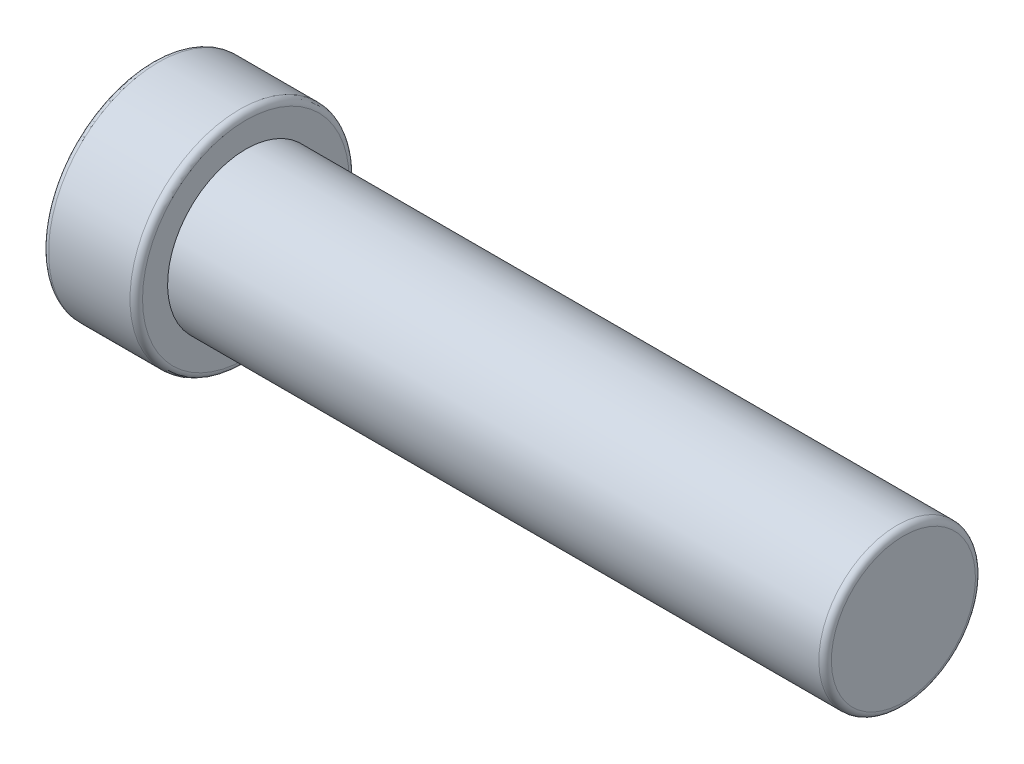
SolidWorks part; units mm, degrees
ref_plane "Ön Düzlem" through (0, 0, 0) normal (0, 0, 1) x (1, 0, 0)
ref_plane "Üst Düzlem" through (0, 0, 0) normal (0, 1, 0) x (1, 0, 0)
ref_plane "Sağ Düzlem" through (0, 0, 0) normal (1, 0, 0) x (0, 0, -1)
sketch "Sketch1" plane through (0, 0, 0) normal (0, 0, 1) x (1, 0, 0)
  line L6 (0, 0) -> (-24, 0)
  line L7 (-24, 0) -> (-24, 3.5)
  line L8 (-24, 3.5) -> (-21, 3.5)
  line L9 (-21, 3.5) -> (-21, 2.5)
  line L10 (-21, 2.5) -> (0, 2.5)
  line L11 (0, 2.5) -> (0, 0)
  dimension "D1" = 2.5
  dimension "D2" = 3.5
  dimension "D3" = 21
  dimension "D4" = 3
revolve "Revolve1" add sketch "Sketch1" angle 360 about L6
fillet "Fillet1" radius 0.2 3 edges at (0, 2.5, 0) (-21, 3.5, 0) (-24, 3.5, 0)
sketch "Sketch2" plane through (-24, 0, 0) normal (-1, 0, 0) x (0, 0, 1)
  line L1 (0, 2) -> (-1.7321, 1)
  line L2 (-1.7321, 1) -> (-1.7321, -1)
  line L3 (-1.7321, -1) -> (0, -2)
  line L4 (0, -2) -> (1.7321, -1)
  line L5 (1.7321, -1) -> (1.7321, 1)
  line L6 (1.7321, 1) -> (0, 2)
  circle A0 centre (0, 0) radius 1.7321 construction
  point P1 (0, 2.0823)
  dimension "D1" = 2
extrude "Cut-Extrude1" cut sketch "Sketch2" against normal blind 3
